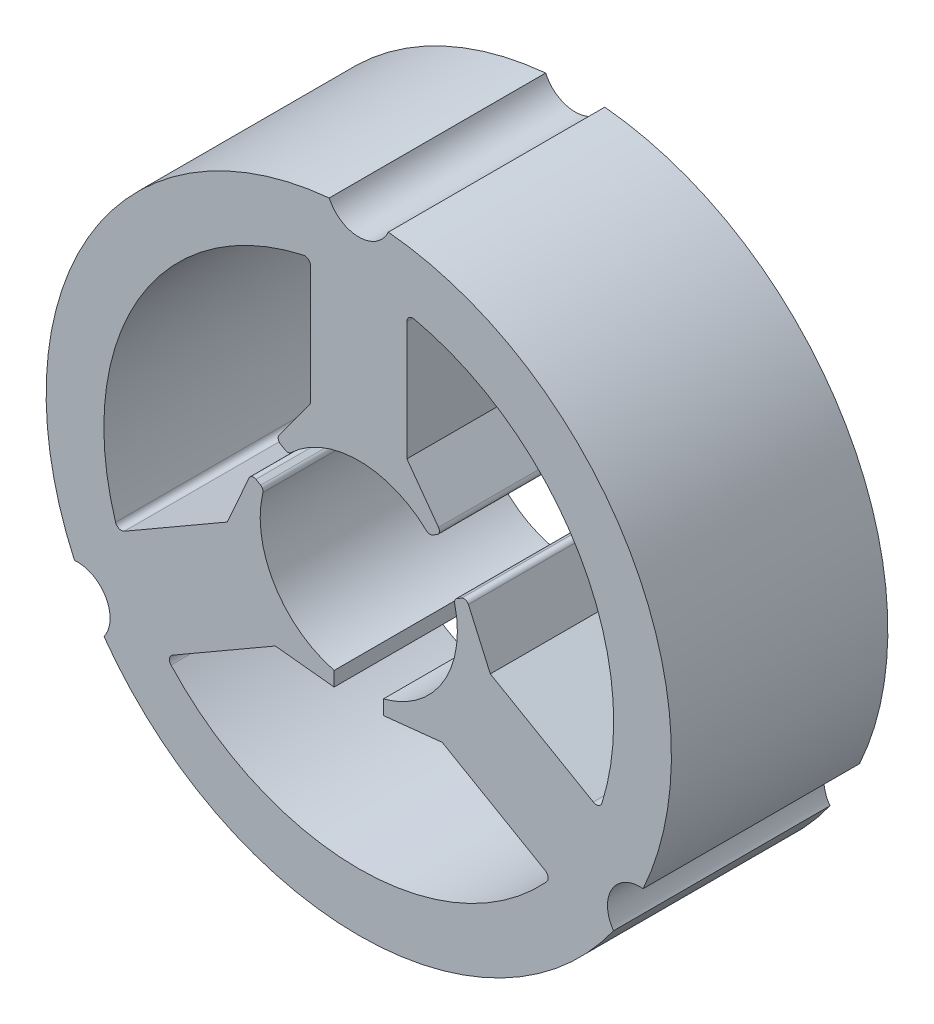
SolidWorks part; units mm, degrees
ref_plane "前视基准面" through (0, 0, 0) normal (0, 0, 1) x (1, 0, 0)
ref_plane "上视基准面" through (0, 0, 0) normal (0, 1, 0) x (1, 0, 0)
ref_plane "右视基准面" through (0, 0, 0) normal (1, 0, 0) x (0, 0, -1)
sketch "草图1" plane through (0, 0, 0) normal (0, 0, 1) x (1, 0, 0)
  line L0 (-21.4536, 0) -> (25.5305, 0) construction
  line L1 (0, 19.7631) -> (0, -19.5145) construction
  line L14 (-0.6212, 13.5) -> (0.4164, 13.5) construction
  line L15 (12.0019, -6.2121) -> (11.4831, -7.1106) construction
  line L16 (-11.3808, -7.2879) -> (-11.8995, -6.3894) construction
  line L17 (0, 0) -> (14.054, -8.1141) construction
  line L18 (0, 0) -> (-15.2933, -8.8296) construction
  circle A1 centre (0, 0) radius 4.1
  arc A7 (-1.2292, 12.9418) -> (-11.8225, -5.4064) centre (0, 0) ccw
  arc A8 (-1.2292, 12.9418) -> (1.2292, 12.9418) centre (0, 13.5) ccw
  arc A9 (11.8225, -5.4064) -> (10.5933, -7.5354) centre (11.6913, -6.75) ccw
  arc A10 (-10.5933, -7.5354) -> (-11.8225, -5.4064) centre (-11.6913, -6.75) ccw
  arc A11 (11.8225, -5.4064) -> (1.2292, 12.9418) centre (0, 0) ccw
  arc A12 (-10.5933, -7.5354) -> (10.5933, -7.5354) centre (0, 0) ccw
  point P24 (0, 0)
  point P31 (0, 0)
  dimension "D1" = 26
  dimension "D2" = 8.2
  dimension "D3" = 1.35
  dimension "D4" = 13.5
  dimension "D7" = 120
  dimension "D5" = 3
  dimension "D6" = 120
extrude "凸台-拉伸1" add sketch "草图1" along normal blind 9
sketch "草图2" plane through (0, 0, 0) normal (0, 0, 1) x (1, 0, 0)
  line L0 (-18.2914, 0) -> (18.1831, 0) construction
  line L1 (0, 18.2481) -> (0, -17.8941) construction
  line L2 (0, 0) -> (17.402, -10.0471) construction
  line L3 (-7.749, -6.7833) -> (-3.47, -4.3128)
  line L4 (-3.47, -4.3128) -> (-1.025, -4.5698)
  line L5 (0, 0) -> (-16.8155, -9.7084) construction
  line L6 (-1.025, -4.5698) -> (-1.025, -3.9698)
  line L7 (1.025, -4.5698) -> (1.025, -3.9698)
  line L8 (3.47, -4.3128) -> (1.025, -4.5698)
  line L9 (7.749, -6.7833) -> (3.47, -4.3128)
  arc A0 (-7.8082, -7.1689) -> (7.8082, -7.1689) centre (0, 0) ccw
  arc A3 (7.8082, -7.1689) -> (7.749, -6.7833) centre (7.624, -6.9998) ccw
  arc A4 (-7.8082, -7.1689) -> (-7.749, -6.7833) centre (-7.624, -6.9998) cw
  arc A7 (-1.025, -3.9698) -> (1.025, -3.9698) centre (0, 0) ccw
  point P19 (1.025, -4.2698)
  point P21 (8.015, -6.9369)
  point P24 (-8.015, -6.9369)
  dimension "D2" = 21.2
  dimension "D8" = 0.25
  dimension "D11" = 0.25
  dimension "D12" = 4.1
  dimension "D1" = 120
  dimension "D3" = 120
  dimension "D4" = 2
  dimension "D5" = 144
  dimension "D6" = 2.05
  dimension "D7" = 0.6
  dimension "D9" = 2
  dimension "D10" = 60
extrude "切除-拉伸1" cut sketch "草图2" along normal blind 10
pattern_circular "阵列(圆周)1" count 3 over 360 about axis through (0, 0, 0) along (0, 0, 1) of "切除-拉伸1"
fillet "圆角1" radius 0.2 8 edges at (-2.9255, 2.8726, 4.5) (-3.4451, 3.1726, 4.5) (4.4701, 1.3972, 4.5) (3.9505, 1.0972, 4.5) (3.4451, 3.1726, 4.5) (2.9255, 2.8726, 4.5) (-3.9505, 1.0972, 4.5) (-4.4701, 1.3972, 4.5)
